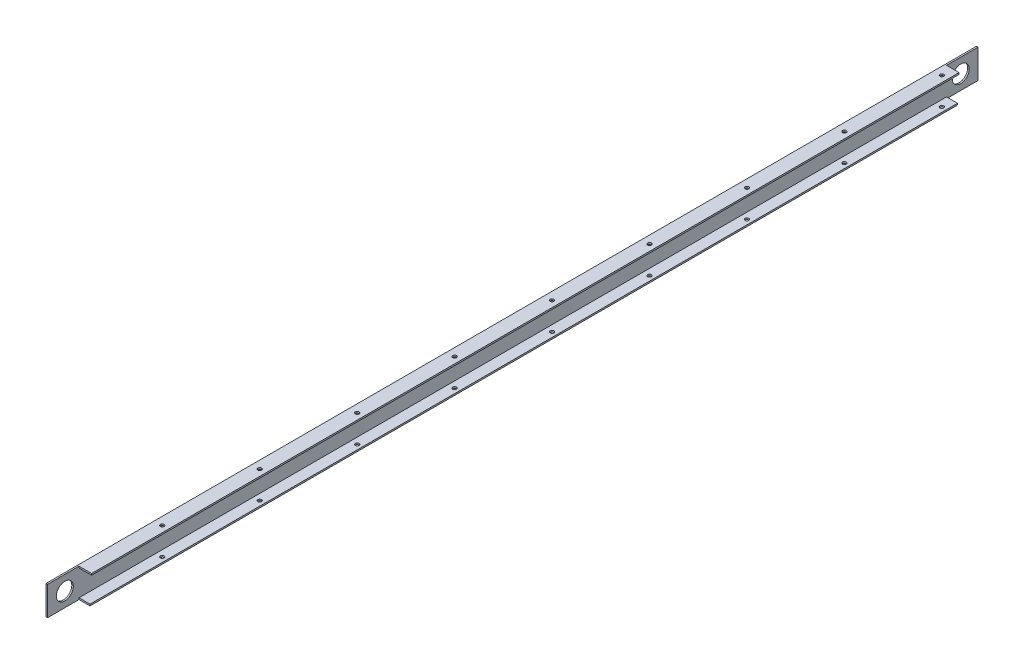
SolidWorks part; units mm, degrees
ref_plane "Plan de face" through (0, 0, 0) normal (0, 0, 1) x (1, 0, 0)
ref_plane "Plan de dessus" through (0, 0, 0) normal (0, 1, 0) x (1, 0, 0)
ref_plane "Plan de droite" through (0, 0, 0) normal (1, 0, 0) x (0, 0, -1)
sketch "Esquisse1" plane through (0, 0, 0) normal (0, 0, 1) x (1, 0, 0)
  line L0 (-3.6003, 0) -> (36.3997, 0)
  line L1 (36.3997, 0) -> (36.3997, 5)
  line L2 (36.3997, 5) -> (1.3997, 5)
  line L3 (1.3997, 5) -> (1.3997, 87)
  line L4 (1.3997, 87) -> (41.3997, 87)
  line L5 (41.3997, 87) -> (41.3997, 92)
  line L6 (41.3997, 92) -> (-3.6003, 92)
  line L7 (-3.6003, 92) -> (-3.6003, 0)
  dimension "D1" = 5
  dimension "D2" = 5
  dimension "D3" = 5
  dimension "D4" = 92
  dimension "D5" = 45
  dimension "D6" = 40
extrude "Boss.-Extru.1" add sketch "Esquisse1" along normal blind 2960
sketch "Esquisse2" plane through (-3.6003, 0, 0) normal (-1, 0, 0) x (0, 0, 1)
  line L1 (2960, 92) -> (0, 92) construction
  line L3 (2960, 0) -> (0, 0) construction
  line L4 (2605, 76) -> (2605, 16) construction
  line L5 (2585, 92) -> (2585, 0) construction
  line L6 (2135, 92) -> (2135, 0) construction
  line L7 (1685, 92) -> (1685, 0) construction
  line L8 (1665, 76) -> (1665, 16) construction
  line L9 (185, 92) -> (185, 0) construction
  line L10 (-1295, 76) -> (-1295, 16) construction
  line L11 (-1315, 92) -> (-1315, 0) construction
  line L12 (-2595, 92) -> (-2595, 0) construction
  line L13 (-3875, 92) -> (-3875, 0) construction
  line L14 (-3895, 76) -> (-3895, 16) construction
  line L18 (2960, 92) -> (2960, 0) construction
  circle A0 centre (2605, 76) radius 4.5
  circle A1 centre (2605, 16) radius 4.5
  circle A2 centre (2565, 16) radius 4.5
  circle A3 centre (2565, 76) radius 4.5
  circle A4 centre (1705, 76) radius 4.5
  circle A5 centre (1705, 16) radius 4.5
  circle A6 centre (1665, 16) radius 4.5
  circle A7 centre (1665, 76) radius 4.5
  circle A8 centre (-1295, 76) radius 4.5
  circle A9 centre (-1295, 16) radius 4.5
  circle A10 centre (-1335, 16) radius 4.5
  circle A11 centre (-1335, 76) radius 4.5
  circle A12 centre (-3855, 76) radius 4.5
  circle A13 centre (-3855, 16) radius 4.5
  circle A14 centre (-3895, 16) radius 4.5
  circle A15 centre (-3895, 76) radius 4.5
  dimension "D1" = 9
  dimension "D4" = 9
  dimension "D2" = 16
  dimension "D3" = 375
  dimension "D5" = 16
  dimension "D6" = 20
  dimension "D7" = 3000
  dimension "D8" = 900
  dimension "D9" = 2560
sketch "Esquisse7" plane through (0, 92, 0) normal (0, 1, 0) x (1, 0, 0)
  line L0 (41.3997, 0) -> (-3.6003, 0) construction
  line L1 (-3.6003, -2960) -> (-3.6003, 0) construction
  circle A0 centre (21.3997, -135) radius 6
  dimension "D1" = 12
  dimension "D2" = 135
  dimension "D3" = 25
extrude "Enlèv. mat.-Extru.2" cut sketch "Esquisse7" against normal through all
sketch "Esquisse8" plane through (0, 92, 0) normal (0, 1, 0) x (1, 0, 0)
  line L0 (-3.6003, -2960) -> (-3.6003, 0) construction
  line L1 (41.3997, -2960) -> (1.3997, -2960)
  line L2 (41.3997, -2960) -> (41.3997, -2860)
  line L3 (41.3997, -2860) -> (1.3997, -2860)
  line L4 (1.3997, -2960) -> (1.3997, -2860)
  line L6 (41.3997, 0) -> (1.3997, 0)
  line L7 (41.3997, 0) -> (41.3997, -100)
  line L8 (41.3997, -100) -> (1.3997, -100)
  line L9 (1.3997, 0) -> (1.3997, -100)
  dimension "D1" = 100
  dimension "D2" = 5
  dimension "D3" = 100
  dimension "D4" = 5
extrude "Enlèv. mat.-Extru.3" cut sketch "Esquisse8" against normal through all
pattern_linear "Répétition linéaire1" count 24 spacing 310 along (0, 0, 1) of "Enlèv. mat.-Extru.2"
sketch "Esquisse9" plane through (-3.6003, 0, 0) normal (-1, 0, 0) x (0, 0, 1)
  line L0 (0, 92) -> (0, 0) construction
  line L1 (2960, 0) -> (0, 0) construction
  line L2 (1480, 92) -> (1480, -163.3323) construction
  line L3 (2960, 92) -> (0, 92) construction
  circle A0 centre (55, 46) radius 27
  circle A1 centre (2905, 46) radius 27
  dimension "D1" = 54
  dimension "D2" = 55
  dimension "D3" = 46
extrude "Enlèv. mat.-Extru.4" cut sketch "Esquisse9" against normal through all
